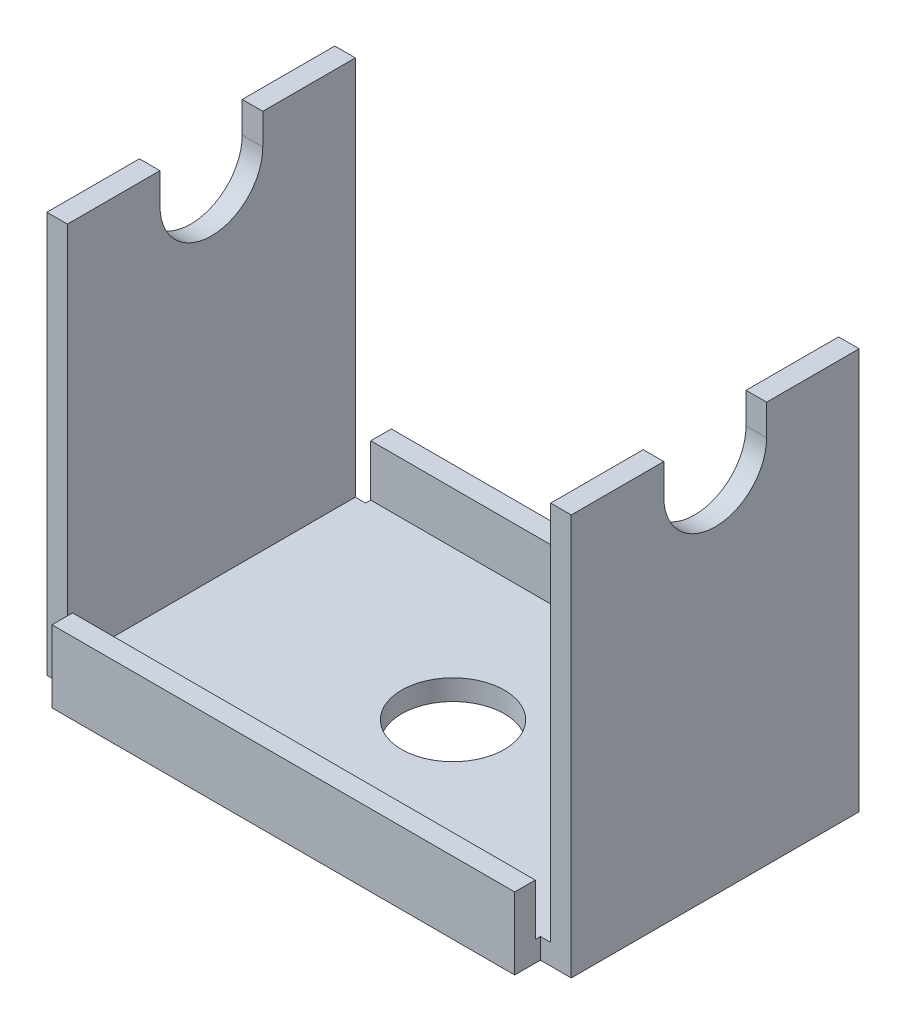
SolidWorks part; units mm, degrees
ref_plane "Front Plane" through (0, 0, 0) normal (0, 0, 1) x (1, 0, 0)
ref_plane "Top Plane" through (0, 0, 0) normal (0, 1, 0) x (1, 0, 0)
ref_plane "Right Plane" through (0, 0, 0) normal (1, 0, 0) x (0, 0, -1)
sketch "Sketch1" plane through (0, 0, 0) normal (0, 0, 1) x (1, 0, 0)
  line L0 (-25.5, 39) -> (-25.5, 0)
  line L1 (-25.5, 0) -> (25.5, 0)
  line L2 (25.5, 0) -> (25.5, 39)
  line L3 (25.5, 39) -> (23.5, 39)
  line L4 (23.5, 39) -> (23.5, 2)
  line L5 (23.5, 2) -> (-23.5, 2)
  line L6 (-23.5, 2) -> (-23.5, 39)
  line L7 (-23.5, 39) -> (-25.5, 39)
  dimension "D2" = 51
  dimension "D3" = 2
  dimension "D4" = 39
  dimension "D5" = 2
extrude "Boss-Extrude1" add sketch "Sketch1" against normal mid plane 28
sketch "Sketch2" plane through (0, 0, 0) normal (1, 0, 0) x (0, 0, -1)
  line L0 (-14, 0) -> (-16.5, 0)
  line L1 (14, 0) -> (-14, 0) construction
  line L2 (-16.5, 0) -> (-16.5, 7)
  line L3 (-16.5, 7) -> (-14.5, 7)
  line L4 (-14.5, 7) -> (-14.5, 2)
  line L5 (-14.5, 2) -> (-14, 2)
  line L6 (-14, 2) -> (-14, 0)
  dimension "D1" = 2
  dimension "D2" = 0.5
  dimension "D3" = 7
extrude "Boss-Extrude2" add sketch "Sketch2" along normal mid plane 45
mirror "Mirror1" about plane through (0, 0, 0) normal (0, 0, 1) of "Boss-Extrude2"
sketch "Sketch3" plane through (25.5, 0, 0) normal (1, 0, 0) x (0, 0, -1)
  line L0 (14, 0) -> (-14, 0) construction
  line L1 (-5, 36) -> (-5, 39)
  line L2 (14, 39) -> (-14, 39) construction
  line L3 (5, 36) -> (5, 39)
  line L4 (0, 0) -> (0, 36) construction
  line L5 (-5, 39) -> (5, 39)
  arc A0 (-5, 36) -> (5, 36) centre (0, 36) ccw
  dimension "D1" = 10
  dimension "D2" = 36
extrude "Cut-Extrude1" cut sketch "Sketch3" against normal through all
sketch "Sketch4" plane through (0, 2, 0) normal (0, 1, 0) x (1, 0, 0)
  line L0 (0, 0) -> (-23.5, 0) construction
  line L1 (-23.5, -5) -> (-23.5, 5) construction
  line L2 (-23.5, 14) -> (-23.5, -14) construction
  circle A0 centre (0, 0) radius 5
  dimension "D1" = 10
extrude "Cut-Extrude2" cut sketch "Sketch4" against normal through all
